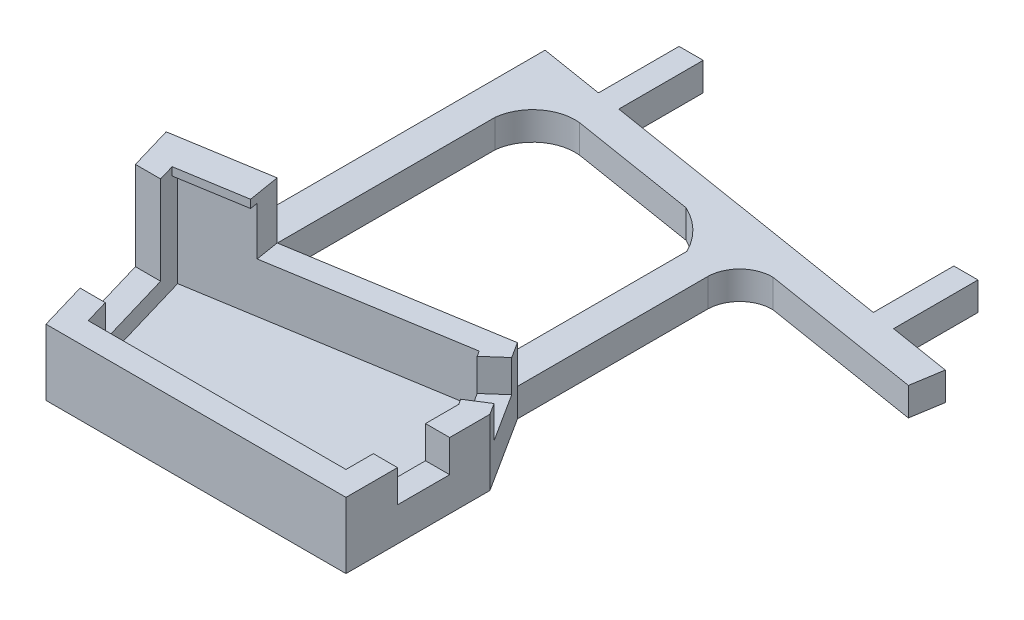
SolidWorks part; units mm, degrees
ref_plane "Front Plane" through (0, 0, 0) normal (0, 0, 1) x (1, 0, 0)
ref_plane "Top Plane" through (0, 0, 0) normal (0, 1, 0) x (1, 0, 0)
ref_plane "Right Plane" through (0, 0, 0) normal (1, 0, 0) x (0, 0, -1)
sketch "Sketch1" plane through (0, 0, 0) normal (0, 1, 0) x (1, 0, 0)
  line L0 (-12.0395, 5.1878) -> (-9.7238, -2.6784)
  line L1 (-9.7238, -2.6784) -> (6.2762, -2.6784)
  line L2 (6.2762, -2.6784) -> (6.2762, 4.3216)
  line L3 (6.2762, 4.3216) -> (4.0463, 7.8216)
  line L4 (-12.0395, 5.1878) -> (4.0463, 7.8216)
  line L5 (-13.9582, 6.3936) -> (4.7799, 9.4616)
  line L6 (4.7799, 9.4616) -> (7.7762, 4.7588)
  line L7 (7.7762, 4.7588) -> (7.7762, -4.1784)
  line L8 (7.7762, -4.1784) -> (-10.8459, -4.1784)
  line L9 (-13.9582, 6.3936) -> (-10.8459, -4.1784)
  dimension "D1" = 8.2
  dimension "D2" = 16
  dimension "D3" = 7
  dimension "D4" = 4.15
  dimension "D5" = 16.3
  dimension "D6" = 1.5
  dimension "D7" = 1.5
  dimension "D8" = 1.5
  dimension "D9" = 1.5
  dimension "D10" = 1.5
  dimension "D11" = 10.5
extrude "Boss-Extrude4" add sketch "Sketch1" along normal blind 1.1
sketch "Sketch4" plane through (0, 1.1, 0) normal (0, 1, 0) x (1, 0, 0)
  line L0 (4.2639, 7.48) -> (5.4033, 8.4832)
  line L1 (6.2762, -2.6784) -> (6.2762, 4.3216) construction
  line L2 (7.7762, 4.7588) -> (7.7762, -4.1784) construction
  line L3 (6.2762, -0.9784) -> (7.7762, -0.9784)
  line L4 (6.2762, 4.3216) -> (4.0463, 7.8216) construction
  line L5 (4.7799, 9.4616) -> (7.7762, 4.7588) construction
  line L6 (7.7762, -4.1784) -> (-10.8459, -4.1784) construction
  line L7 (4.2639, 7.48) -> (4.0463, 7.8216)
  line L8 (4.0463, 7.8216) -> (-12.0395, 5.1878)
  line L9 (-9.7238, -2.6784) -> (-10.1654, -1.1784)
  line L10 (-9.7238, -2.6784) -> (6.2762, -2.6784)
  line L11 (6.2762, -2.6784) -> (6.2762, -0.9784)
  line L12 (5.4033, 8.4832) -> (4.7799, 9.4616)
  line L13 (4.7799, 9.4616) -> (-13.9582, 6.3936)
  line L14 (-12.0395, 5.1878) -> (-9.7238, -2.6784) construction
  line L15 (-10.8459, -4.1784) -> (7.7762, -4.1784)
  line L16 (7.7762, -4.1784) -> (7.7762, -0.9784)
  line L17 (-10.1654, -1.1784) -> (-11.729, -1.1784)
  line L18 (-13.9582, 6.3936) -> (-10.8459, -4.1784) construction
  line L19 (-11.729, -1.1784) -> (-10.8459, -4.1784)
  line L20 (-12.0395, 5.1878) -> (-11.5979, 3.6878)
  line L21 (-11.5979, 3.6878) -> (-13.1616, 3.6878)
  line L22 (-13.1616, 3.6878) -> (-13.9582, 6.3936)
  line L23 (6.2762, 2.2588) -> (6.2762, 4.3216)
  line L24 (6.2762, 4.3216) -> (6.0613, 4.6589)
  line L25 (7.7762, 2.2588) -> (6.2762, 2.2588)
  line L26 (6.0613, 4.6589) -> (7.3263, 5.4649)
  line L27 (7.3263, 5.4649) -> (7.7762, 4.7588)
  line L28 (7.7762, 4.7588) -> (7.7762, 2.2588)
  dimension "D1" = 3.2
  dimension "D2" = 3
  dimension "D3" = 1.5
  dimension "D4" = 0.4
  dimension "D5" = 2.5
extrude "Boss-Extrude6" add sketch "Sketch4" along normal blind 2
sketch "Sketch8" plane through (0, 0, 0) normal (0, -1, 0) x (1, 0, 0)
  line L0 (4.7799, -9.4616) -> (-13.9582, -6.3936)
  line L1 (-13.9582, -6.3936) -> (-10.8459, 4.1784)
  line L2 (-10.8459, 4.1784) -> (7.7762, 4.1784)
  line L3 (7.7762, 4.1784) -> (7.7762, -4.7588)
  line L4 (7.7762, -4.7588) -> (4.7799, -9.4616)
extrude "Boss-Extrude8" add sketch "Sketch8" along normal blind 1
sketch "Sketch12" plane through (0, 3.1, 0) normal (0, 1, 0) x (1, 0, 0)
  line L0 (-13.9582, 6.3936) -> (-8.037, 7.3631)
  line L1 (4.7799, 9.4616) -> (-13.9582, 6.3936) construction
  line L2 (-8.037, 7.3631) -> (-7.7946, 5.8828)
  line L3 (-12.0395, 5.1878) -> (4.0463, 7.8216) construction
  line L4 (-7.7946, 5.8828) -> (-12.0395, 5.1878)
  line L5 (-12.0395, 5.1878) -> (-11.5979, 3.6878)
  line L6 (-11.5979, 3.6878) -> (-13.1616, 3.6878)
  line L7 (-13.1616, 3.6878) -> (-13.9582, 6.3936)
  dimension "D1" = 6
extrude "Boss-Extrude9" add sketch "Sketch12" along normal blind 3.5
sketch "Sketch13" plane through (-1.1416, 0, -6.9721) normal (0.1616, 0, 0.9869) x (0.9869, 0, -0.1616)
  line L0 (-6.7417, 6.6) -> (-6.7417, 6.1)
  line L1 (-6.7417, 6.6) -> (-6.7417, 3.1) construction
  line L2 (-6.7417, 6.1) -> (-11.0431, 6.1)
  line L3 (-11.0431, 6.6) -> (-11.0431, 0) construction
  line L4 (-11.0431, 6.1) -> (-11.0431, 6.6)
  line L5 (-11.0431, 6.6) -> (-6.7417, 6.6)
  dimension "D1" = 0.5
extrude "Boss-Extrude10" add sketch "Sketch13" along normal blind 0.5
sketch "Sketch14" plane through (0, -1, 0) normal (0, -1, 0) x (1, 0, 0)
  line L0 (-12.4357, -28.3936) -> (-8.4817, -27.7564)
  line L1 (-13.9582, -6.3936) -> (4.7799, -9.4616) construction
  line L2 (-12.4357, -28.3936) -> (-12.4357, -9.1342)
  line L3 (-10.3785, -6.9797) -> (-10.3785, -23.2398)
  line L4 (-10.3785, -6.9797) -> (-13.9582, -6.3936)
  line L5 (-7.4698, -25.5675) -> (0.417, -24.2966)
  line L6 (2.7799, -11.4021) -> (2.7799, -21.9824)
  line L7 (0.6679, -8.7884) -> (4.7799, -9.4616)
  line L8 (17.1822, -23.6207) -> (16.864, -21.6462)
  line L9 (16.864, -21.6462) -> (6.8432, -23.261)
  line L10 (4.7799, -21.3029) -> (4.7799, -9.4616)
  line L11 (-8.4817, -27.7564) -> (-8.4817, -32.7564)
  line L12 (-8.4817, -32.7564) -> (-6.9817, -32.7564)
  line L13 (-6.9817, -32.7564) -> (-6.9817, -27.5147)
  line L14 (-6.9817, -27.5147) -> (11.8536, -24.4794)
  line L15 (11.8536, -24.4794) -> (11.8536, -29.4794)
  line L16 (11.8536, -29.4794) -> (13.3536, -29.4794)
  line L17 (13.3536, -29.4794) -> (13.3536, -24.2377)
  line L18 (13.3536, -24.2377) -> (17.1822, -23.6207)
  arc A0 (-13.9582, -6.3936) -> (-12.4357, -9.1342) centre (-16.9159, -9.8298) cw
  arc A1 (-10.3785, -23.2398) -> (-7.4698, -25.5675) centre (-7.7602, -22.9493) ccw
  arc A2 (0.417, -24.2966) -> (2.7799, -21.9824) centre (-1.71, -19.7615) ccw
  arc A3 (4.7799, -21.3029) -> (6.8432, -23.261) centre (6.7906, -21.2503) ccw
  arc A4 (2.7799, -11.4021) -> (0.6679, -8.7884) centre (-0.6652, -12.0257) ccw
  dimension "D4" = 1.5
  dimension "D1" = 30
  dimension "D2" = 1.5
  dimension "D3" = 22
  dimension "D5" = 5
  dimension "D6" = 5
extrude "Boss-Extrude11" add sketch "Sketch14" against normal blind 1.75
